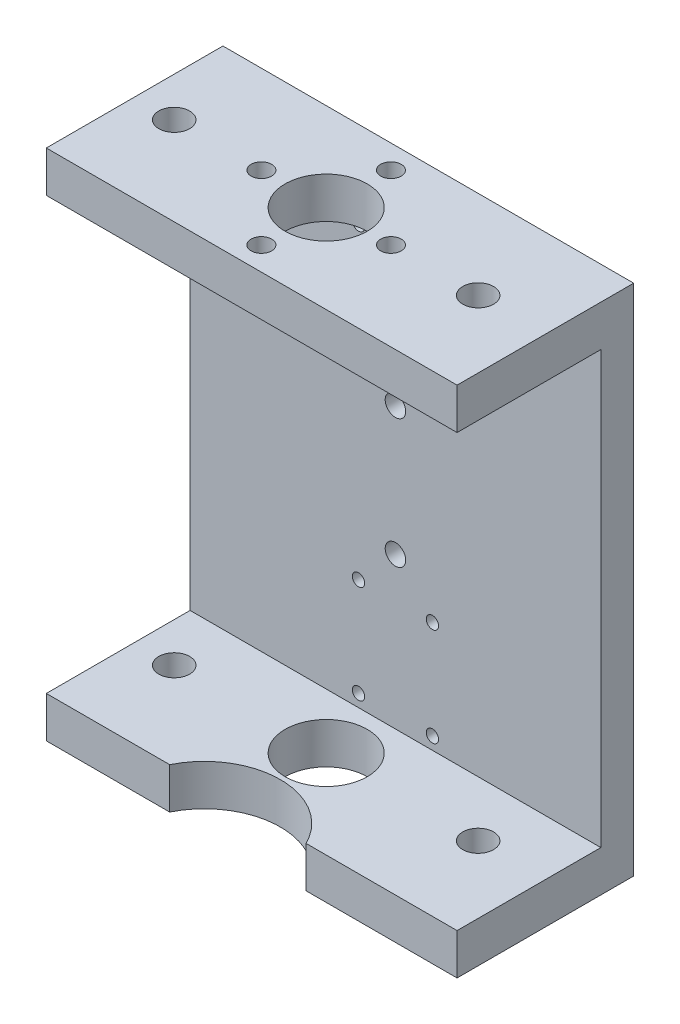
SolidWorks part; units mm, degrees
ref_plane "Front Plane" through (0, 0, 0) normal (0, 0, 1) x (1, 0, 0)
ref_plane "Top Plane" through (0, 0, 0) normal (0, 1, 0) x (1, 0, 0)
ref_plane "Right Plane" through (0, 0, 0) normal (1, 0, 0) x (0, 0, -1)
sketch "Sketch2" plane through (0, 0, 0) normal (0, 0, 1) x (1, 0, 0)
  line L5 (9, -8.0356) -> (-9, -31.9644) construction
  line L6 (-50, 80) -> (50, 80)
  line L7 (-50, 80) -> (-50, -45)
  line L8 (-50, -45) -> (50, -45)
  line L9 (50, 80) -> (50, -45)
  line L10 (-9, -8.0356) -> (9, -31.9644) construction
  line L12 (-9, 66.9644) -> (9, 43.0356) construction
  line L13 (-9, 43.0356) -> (9, 66.9644) construction
  circle A7 centre (-9, -8.0356) radius 1.5
  circle A12 centre (9, -31.9644) radius 1.5
  circle A13 centre (9, -8.0356) radius 1.5
  circle A18 centre (-9, -31.9644) radius 1.5
  circle A27 centre (9, 43.0356) radius 1.5
  circle A28 centre (-9, 43.0356) radius 1.5
  circle A29 centre (-9, 66.9644) radius 1.5
  circle A30 centre (9, 66.9644) radius 1.5
  circle A31 centre (0, 33.18) radius 2.5
  circle A32 centre (0, 1.82) radius 2.5
  point P5 (0, 0)
  point P22 (0, 17.5)
  dimension "D2" = 125
extrude "Boss-Extrude1" add sketch "Sketch2" along normal blind 8
sketch "Sketch5" plane through (0, 0, 8) normal (0, 0, 1) x (1, 0, 0)
  line L8 (-50, 70) -> (-50, 80)
  line L10 (-50, 80) -> (50, 80)
  line L13 (50, -45) -> (50, 80) construction
  line L14 (50, 70) -> (-50, 70)
  line L19 (50, 80) -> (50, 70)
  line L22 (-50, 80) -> (-50, -45) construction
  line L24 (-50, -35) -> (-50, -45)
  line L25 (50, -35) -> (-50, -35)
  line L26 (50, -45) -> (50, -35)
  line L29 (-50, -45) -> (50, -45)
extrude "Boss-Extrude2" add sketch "Sketch5" along normal blind 35
sketch "Sketch7" plane through (0, 80, 0) normal (0, 1, 0) x (1, 0, 0)
  circle A0 centre (-3.365, -21.5) radius 10
  circle A1 centre (-40.365, -21.5) radius 3.75
  circle A2 centre (33.635, -21.5) radius 3.75
  dimension "D1" = 20
  dimension "D4" = 7.5
  dimension "D5" = 7.5
extrude "Cut-Extrude2" cut sketch "Sketch7" against normal blind 290
sketch "Sketch8" plane through (0, -35, 0) normal (0, 1, 0) x (1, 0, 0)
  circle A4 centre (-3.365, -51.1648) radius 18.5
  dimension "D1" = 37
extrude "Cut-Extrude5" cut sketch "Sketch8" against normal through all
sketch "Sketch9" plane through (0, 80, 0) normal (0, 1, 0) x (1, 0, 0)
  line L0 (-3.365, -21.5) -> (-3.365, -43) construction
  line L1 (50, -43) -> (-50, -43) construction
  line L2 (-3.365, -43) -> (-3.365, 0) construction
  line L3 (50, 0) -> (-50, 0) construction
  line L4 (-3.365, 0) -> (-3.365, -21.5) construction
  line L5 (-3.365, -21.5) -> (21.9905, -21.5) construction
  line L6 (21.9905, -21.5) -> (-23.6262, -21.5) construction
  circle A0 centre (-3.365, -5.73) radius 2.5
  circle A1 centre (12.405, -21.5) radius 2.5
  circle A2 centre (-19.135, -21.5) radius 2.5
  circle A3 centre (-3.365, -37.27) radius 2.5
extrude "Cut-Extrude6" cut sketch "Sketch9" against normal blind 20
